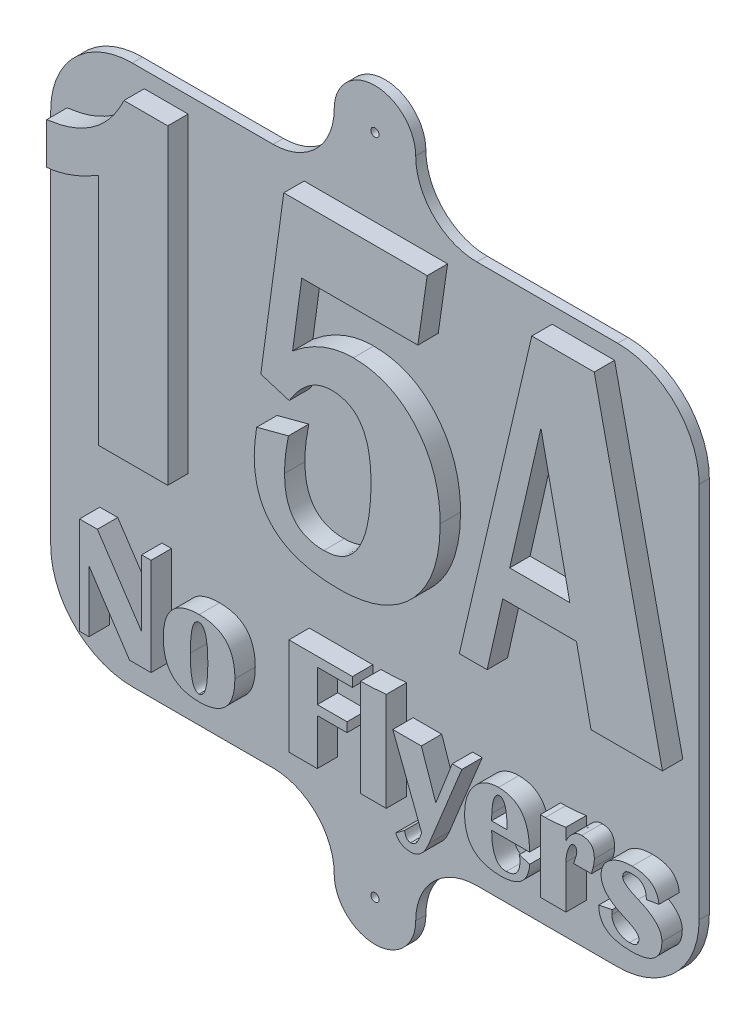
SolidWorks part; units mm, degrees
ref_plane "Front Plane" through (0, 0, 0) normal (0, 0, 1) x (1, 0, 0)
ref_plane "Top Plane" through (0, 0, 0) normal (0, 1, 0) x (1, 0, 0)
ref_plane "Right Plane" through (0, 0, 0) normal (1, 0, 0) x (0, 0, -1)
sketch "Sketch2" plane through (0, 0, 0) normal (0, 0, 1) x (1, 0, 0)
  line L0 (-33.1391, 3.1236) -> (-24.6504, 3.1236)
  line L1 (-43.75, -43.75) -> (43.75, -43.75)
  line L2 (-43.75, -43.75) -> (-43.75, 43.75)
  line L3 (-43.75, 43.75) -> (43.75, 43.75)
  line L4 (43.75, -43.75) -> (43.75, 43.75)
  line L6 (-43.75, 43.75) -> (-5.7811, 5.7811) construction
  line L7 (-35.4802, -17.7994) -> (-34.3196, -17.7994)
  line L8 (-24.6504, 41.3228) -> (-24.6504, 3.1236)
  line L9 (-24.6504, 3.1236) -> (-33.1391, 3.1236)
  line L10 (-33.1391, 3.1236) -> (-33.1391, 31.8144)
  line L11 (-39.5056, 29.485) -> (-39.5056, 34.5501)
  line L12 (-30.0304, 41.3228) -> (-24.6504, 41.3228)
  line L13 (7.1823, 41.3228) -> (6.0383, 33.3646)
  line L14 (6.0383, 33.3646) -> (-8.2118, 33.3646)
  line L15 (-8.2118, 33.3646) -> (-9.3392, 25.05)
  line L16 (-13.7411, 14.7541) -> (-9.8449, 15.782)
  line L17 (-9.7537, 19.5787) -> (-13.2354, 20.6481)
  line L18 (-13.2354, 20.6481) -> (-10.4169, 41.3228)
  line L19 (-10.4169, 41.3228) -> (7.1823, 41.3228)
  line L20 (27.6746, 41.3228) -> (36.0472, 3.1236)
  line L21 (36.0472, 3.1236) -> (27.285, 3.1236)
  line L22 (27.285, 3.1236) -> (25.4944, 11.6123)
  line L23 (25.4944, 11.6123) -> (16.4502, 11.6123)
  line L24 (16.4502, 11.6123) -> (14.5353, 3.1236)
  line L25 (14.5353, 3.1236) -> (11.1199, 3.1236)
  line L26 (11.1199, 3.1236) -> (20.0148, 41.3228)
  line L27 (20.0148, 41.3228) -> (27.6746, 41.3228)
  line L28 (17.3041, 15.3261) -> (24.682, 15.3261)
  line L29 (24.682, 15.3261) -> (21.134, 32.088)
  line L30 (21.134, 32.088) -> (17.3041, 15.3261)
  line L31 (-26.693, -5.8621) -> (-26.693, -17.7994)
  line L32 (-26.693, -17.7994) -> (-29.338, -17.7994)
  line L33 (-29.338, -17.7994) -> (-34.3196, -10.2687)
  line L34 (-34.3196, -10.2687) -> (-34.3196, -17.7994)
  line L35 (-34.3196, -17.7994) -> (-35.4802, -17.7994)
  line L36 (-35.4802, -17.7994) -> (-35.4802, -5.8621)
  line L37 (-35.4802, -5.8621) -> (-33.2886, -5.8621)
  line L38 (-33.2886, -5.8621) -> (-27.8536, -14.0327)
  line L39 (-27.8536, -14.0327) -> (-27.8536, -5.8621)
  line L40 (-27.8536, -5.8621) -> (-26.693, -5.8621)
  line L41 (-1.9895, -5.8621) -> (-1.9895, -7.0227)
  line L42 (-1.9895, -7.0227) -> (-6.3002, -7.0227)
  line L43 (-6.3002, -7.0227) -> (-6.3002, -11.0018)
  line L44 (-6.3002, -11.0018) -> (-2.6527, -11.0018)
  line L45 (-2.6527, -11.0018) -> (-2.6527, -12.1624)
  line L46 (-2.6527, -12.1624) -> (-6.3002, -12.1624)
  line L47 (-6.3002, -12.1624) -> (-6.3002, -17.7994)
  line L48 (-6.3002, -17.7994) -> (-9.7819, -17.7994)
  line L49 (-9.7819, -17.7994) -> (-9.7819, -5.8621)
  line L50 (-9.7819, -5.8621) -> (-1.9895, -5.8621)
  line L51 (2.1553, -5.6886) -> (2.1553, -17.7994)
  line L52 (2.1553, -17.7994) -> (-0.9948, -17.7994)
  line L53 (-0.9948, -17.7994) -> (-0.9948, -5.8621)
  line L54 (11.4399, -9.0123) -> (7.4012, -18.9133)
  line L55 (3.3081, -19.8226) -> (4.4091, -19.0221)
  line L56 (6.2717, -18.8408) -> (6.5075, -18.2372)
  line L57 (6.5075, -18.2372) -> (2.9584, -9.0123)
  line L58 (2.9584, -9.0123) -> (6.4634, -9.0123)
  line L59 (6.4634, -9.0123) -> (8.238, -14.1804)
  line L60 (8.238, -14.1804) -> (10.2586, -9.0123)
  line L61 (10.2586, -9.0123) -> (11.4399, -9.0123)
  line L62 (18.4706, -14.5612) -> (19.7555, -14.9368)
  line L63 (19.7374, -13.6545) -> (15.0874, -13.6545)
  line L64 (15.077, -12.6597) -> (16.9836, -12.6597)
  line L65 (15.1133, -11.8463) -> (15.077, -12.6597)
  line L66 (27.3355, -12.1624) -> (25.1517, -12.1624)
  line L67 (24.2061, -12.4965) -> (24.2061, -17.7994)
  line L68 (24.2061, -17.7994) -> (21.056, -17.7994)
  line L69 (21.056, -17.7994) -> (21.056, -9.0123)
  line L70 (21.056, -9.0123) -> (21.67, -9.0123)
  line L71 (24.2061, -8.7817) -> (24.2061, -10.2169)
  line L72 (35.6175, -11.2686) -> (34.0709, -11.5406)
  line L73 (28.2292, -15.0353) -> (29.8742, -14.7063)
  line L74 (-29.338, -17.7994) -> (-26.693, -17.7994)
  line L75 (11.1199, 3.1236) -> (14.5353, 3.1236)
  line L76 (27.285, 3.1236) -> (36.0472, 3.1236)
  line L77 (-9.7819, -17.7994) -> (-6.3002, -17.7994)
  line L78 (-0.9948, -17.7994) -> (2.1553, -17.7994)
  line L79 (6.339, -17.7994) -> (7.8556, -17.7994)
  line L80 (13.5471, 13.5471) -> (43.75, 43.75) construction
  line L81 (21.056, -17.7994) -> (24.2061, -17.7994)
  line L82 (9.9083, -9.9083) -> (43.75, -43.75) construction
  spline S0 degree 3 poles (-33.1391, 31.8144) (-34.1906, 31.1802) (-36.2341, 30.1453) (-38.456, 29.5713) (-39.5056, 29.485) knots 0 0 0 0 0.539332 1 1 1 1
  spline S1 degree 3 poles (-39.5056, 34.5501) (-38.4451, 34.6886) (-36.8913, 35.0188) (-35.0093, 35.8709) (-33.742, 36.6305) (-32.6145, 37.5733) (-31.2534, 39.0609) (-30.464, 40.3838) (-30.0304, 41.3228) knots 0 0 0 0 0.263349 0.386092 0.50611 0.625172 0.745757 1 1 1 1
  spline S2 degree 3 poles (-9.3392, 25.05) (-8.7632, 25.5267) (-7.8787, 26.1871) (-6.6199, 26.8894) (-5.6888, 27.3147) (-4.7523, 27.6494) (-3.4929, 27.9606) (-2.5292, 28.0565) (-1.8867, 28.0592) knots 0 0 0 0 0.273618 0.402083 0.526429 0.647547 0.765176 1 1 1 1
  spline S3 degree 3 poles (-1.8867, 28.0592) (-1.1408, 28.0481) (-0.0301, 27.967) (1.3791, 27.5874) (2.3756, 27.2174) (3.3149, 26.7244) (4.1996, 26.1209) (5.0326, 25.4142) (5.7975, 24.5994) (6.5002, 23.7132) (7.11, 22.7511) (7.6205, 21.7299) (8.0527, 20.6511) (8.3681, 19.5069) (8.6873, 17.8723) (8.7699, 16.6024) (8.7739, 15.7406) knots 0 0 0 0 0.122904 0.181635 0.23943 0.297339 0.355551 0.415172 0.476547 0.538982 0.600861 0.663434 0.72645 0.791596 0.858237 1 1 1 1
  spline S4 degree 3 poles (8.7739, 15.7406) (8.7755, 14.7846) (8.6868, 13.3764) (8.3232, 11.5769) (7.9641, 10.3288) (7.4741, 9.169) (6.909, 8.0702) (6.2105, 7.0658) (5.4251, 6.1354) (4.549, 5.2988) (3.5905, 4.5707) (2.5527, 3.9682) (1.4527, 3.4525) (0.2716, 3.067) (-1.4387, 2.6944) (-2.7758, 2.5967) (-3.6856, 2.593) knots 0 0 0 0 0.140185 0.205865 0.26878 0.330146 0.390105 0.449525 0.508998 0.56829 0.626685 0.684956 0.743842 0.804414 0.86661 1 1 1 1
  spline S5 degree 3 poles (-3.6856, 2.593) (-4.4974, 2.5877) (-5.6755, 2.6554) (-7.1848, 2.8877) (-8.1962, 3.1427) (-9.1394, 3.4364) (-9.9902, 3.8354) (-10.7656, 4.2887) (-11.462, 4.8138) (-12.0705, 5.4148) (-12.5954, 6.0856) (-13.0517, 6.8215) (-13.4099, 7.6356) (-13.6964, 8.5155) (-13.9617, 9.8198) (-14.0436, 10.8436) (-14.0395, 11.546) knots 0 0 0 0 0.15526 0.225408 0.291834 0.354702 0.414082 0.47121 0.526304 0.580516 0.634356 0.688946 0.745744 0.804099 0.865695 1 1 1 1
  spline S6 degree 3 poles (-14.0395, 11.546) (-14.0442, 12.0308) (-13.968, 13.1039) (-13.8394, 14.1714) (-13.7411, 14.7541) knots 0 0 0 0 0.450572 1 1 1 1
  spline S7 degree 3 poles (-9.8449, 15.782) (-9.9946, 15.047) (-10.2261, 13.6411) (-10.3233, 12.2193) (-10.3257, 11.546) knots 0 0 0 0 0.527123 1 1 1 1
  spline S8 degree 3 poles (-10.3257, 11.546) (-10.3201, 10.7021) (-10.2291, 9.4835) (-9.6932, 8.0432) (-9.1555, 7.2077) (-8.4633, 6.5493) (-7.2646, 5.9193) (-6.2165, 5.775) (-5.501, 5.7763) knots 0 0 0 0 0.295855 0.419781 0.532649 0.639755 0.749346 1 1 1 1
  spline S9 degree 3 poles (-5.501, 5.7763) (-5.0453, 5.7816) (-4.3712, 5.8422) (-3.5326, 6.1176) (-2.9627, 6.4023) (-2.439, 6.7696) (-1.9593, 7.2161) (-1.5308, 7.7439) (-1.1343, 8.3417) (-0.81, 9.0338) (-0.5074, 9.7953) (-0.2631, 10.6428) (-0.066, 11.5686) (0.0887, 12.5707) (0.2512, 14.0643) (0.2786, 15.2291) (0.2852, 16.0307) knots 0 0 0 0 0.10375 0.151958 0.199653 0.247862 0.29669 0.347938 0.401879 0.459116 0.521094 0.587794 0.659039 0.735879 0.817906 1 1 1 1
  spline S10 degree 3 poles (0.2852, 16.0307) (0.2866, 16.5977) (0.259, 17.4225) (0.1197, 18.4794) (-0.0109, 19.1881) (-0.1718, 19.8457) (-0.3934, 20.4368) (-0.6256, 20.9865) (-0.9235, 21.4664) (-1.2404, 21.901) (-1.6062, 22.271) (-2.0019, 22.5916) (-2.4512, 22.839) (-2.929, 23.0384) (-3.6371, 23.2319) (-4.1962, 23.2934) (-4.5809, 23.2843) knots 0 0 0 0 0.17174 0.249366 0.322555 0.389926 0.453974 0.513525 0.570203 0.624586 0.67606 0.727282 0.778237 0.830754 0.883736 1 1 1 1
  spline S11 degree 3 poles (-4.5809, 23.2843) (-5.0596, 23.2861) (-5.783, 23.1625) (-6.6885, 22.7745) (-7.3496, 22.3591) (-7.9872, 21.8328) (-8.8502, 20.9425) (-9.4002, 20.1459) (-9.7537, 19.5787) knots 0 0 0 0 0.215337 0.326397 0.442196 0.566126 0.69826 1 1 1 1
  spline S12 degree 3 poles (-20.8021, -8.6807) (-20.4583, -8.6807) (-19.9561, -8.7116) (-19.3169, -8.8346) (-18.8862, -8.9615) (-18.4897, -9.1247) (-18.1268, -9.3249) (-17.7979, -9.5622) (-17.5028, -9.8355) (-17.2447, -10.1473) (-17.021, -10.4945) (-16.8311, -10.8775) (-16.679, -11.2977) (-16.5615, -11.7534) (-16.438, -12.4287) (-16.4188, -12.96) (-16.4137, -13.3229) knots 0 0 0 0 0.140797 0.205276 0.266125 0.324294 0.38047 0.435417 0.489949 0.544674 0.600666 0.658689 0.719308 0.783277 0.851166 1 1 1 1
  spline S13 degree 3 poles (-16.4137, -13.3229) (-16.4188, -13.6858) (-16.438, -14.2172) (-16.5615, -14.8925) (-16.679, -15.3482) (-16.8311, -15.7684) (-17.021, -16.1513) (-17.2447, -16.4986) (-17.5028, -16.8104) (-17.7979, -17.0836) (-18.1268, -17.3209) (-18.4897, -17.5211) (-18.8862, -17.6844) (-19.3169, -17.8113) (-19.9561, -17.9342) (-20.4583, -17.9651) (-20.8021, -17.9652) knots 0 0 0 0 0.148834 0.216723 0.280692 0.341311 0.399334 0.455326 0.510051 0.564583 0.61953 0.675706 0.733875 0.794724 0.859203 1 1 1 1
  spline S14 degree 3 poles (-20.8021, -17.9652) (-21.1467, -17.9651) (-21.65, -17.9346) (-22.2907, -17.8108) (-22.7226, -17.685) (-23.1202, -17.5204) (-23.4846, -17.3216) (-23.8142, -17.0845) (-24.1065, -16.8086) (-24.3676, -16.4996) (-24.591, -16.1513) (-24.7803, -15.7679) (-24.9362, -15.3487) (-25.0539, -14.8927) (-25.1706, -14.2165) (-25.1998, -13.6864) (-25.2009, -13.3229) knots 0 0 0 0 0.141 0.205411 0.266534 0.324641 0.381066 0.435955 0.490171 0.545064 0.600996 0.658958 0.719635 0.783535 0.85129 1 1 1 1
  spline S15 degree 3 poles (-25.2009, -13.3229) (-25.1998, -12.9595) (-25.1706, -12.4294) (-25.0539, -11.7532) (-24.9362, -11.2971) (-24.7803, -10.878) (-24.591, -10.4946) (-24.3676, -10.1462) (-24.1065, -9.8373) (-23.8142, -9.5613) (-23.4846, -9.3243) (-23.1202, -9.1255) (-22.7226, -8.9608) (-22.2907, -8.8351) (-21.65, -8.7112) (-21.1467, -8.6807) (-20.8021, -8.6807) knots 0 0 0 0 0.14871 0.216465 0.280365 0.341042 0.399004 0.454936 0.509829 0.564045 0.618934 0.675359 0.733466 0.794589 0.859 1 1 1 1
  spline S16 degree 3 poles (-20.8125, -9.5096) (-20.8991, -9.5103) (-21.032, -9.5408) (-21.1834, -9.6429) (-21.2888, -9.75) (-21.3837, -9.8867) (-21.4718, -10.0519) (-21.5516, -10.2463) (-21.6197, -10.4717) (-21.6853, -10.7244) (-21.738, -11.0086) (-21.785, -11.3212) (-21.8203, -11.6645) (-21.8473, -12.0369) (-21.8828, -12.5927) (-21.8798, -13.0251) (-21.885, -13.3229) knots 0 0 0 0 0.061623 0.093987 0.128729 0.167924 0.211891 0.261732 0.317091 0.379205 0.447379 0.522509 0.604032 0.692727 0.788081 1 1 1 1
  spline S17 degree 3 poles (-21.885, -13.3229) (-21.8798, -13.6207) (-21.8828, -14.0532) (-21.8473, -14.6089) (-21.8203, -14.9813) (-21.785, -15.3246) (-21.738, -15.6373) (-21.6853, -15.9214) (-21.6197, -16.1742) (-21.5516, -16.3995) (-21.4718, -16.5939) (-21.3837, -16.7592) (-21.2888, -16.8959) (-21.1834, -17.003) (-21.032, -17.1051) (-20.8991, -17.1356) (-20.8125, -17.1362) knots 0 0 0 0 0.211919 0.307273 0.395968 0.477491 0.552621 0.620795 0.682909 0.738268 0.788109 0.832076 0.871271 0.906013 0.938377 1 1 1 1
  spline S18 degree 3 poles (-20.8125, -17.1362) (-20.7251, -17.1358) (-20.5908, -17.1058) (-20.4389, -17.0021) (-20.3306, -16.897) (-20.2367, -16.7583) (-20.1444, -16.5949) (-20.0668, -16.3988) (-19.9932, -16.1752) (-19.9332, -15.9208) (-19.8785, -15.6374) (-19.8331, -15.3244) (-19.7935, -14.9815) (-19.7666, -14.609) (-19.7378, -14.053) (-19.7307, -13.6209) (-19.7296, -13.3229) knots 0 0 0 0 0.062144 0.094462 0.129591 0.16873 0.212928 0.262698 0.318165 0.380042 0.448118 0.523141 0.604614 0.693183 0.788367 1 1 1 1
  spline S19 degree 3 poles (-19.7296, -13.3229) (-19.7307, -13.025) (-19.7378, -12.5929) (-19.7666, -12.0369) (-19.7935, -11.6643) (-19.8331, -11.3215) (-19.8785, -11.0085) (-19.9332, -10.725) (-19.9932, -10.4707) (-20.0668, -10.247) (-20.1444, -10.051) (-20.2367, -9.8875) (-20.3306, -9.7489) (-20.4389, -9.6437) (-20.5908, -9.54) (-20.7251, -9.51) (-20.8125, -9.5096) knots 0 0 0 0 0.211633 0.306817 0.395386 0.476859 0.551882 0.619958 0.681835 0.737302 0.787072 0.83127 0.870409 0.905538 0.937856 1 1 1 1
  spline S20 degree 3 poles (-0.9948, -5.8621) (-0.5143, -5.8633) (0.5373, -5.8234) (1.5862, -5.7414) (2.1553, -5.6886) knots 0 0 0 0 0.45666 1 1 1 1
  spline S21 degree 3 poles (7.4012, -18.9133) (7.2714, -19.2193) (7.0685, -19.6552) (6.7116, -20.1492) (6.4408, -20.441) (6.1481, -20.6664) (5.736, -20.8874) (5.3907, -20.9506) (5.163, -20.9495) knots 0 0 0 0 0.310559 0.44483 0.566674 0.680331 0.787619 1 1 1 1
  spline S22 degree 3 poles (5.163, -20.9495) (4.9526, -20.9482) (4.6445, -20.9201) (4.2629, -20.801) (4.0155, -20.6728) (3.7919, -20.5159) (3.5326, -20.2444) (3.3847, -19.9997) (3.3081, -19.8226) knots 0 0 0 0 0.27306 0.397686 0.515848 0.632977 0.750149 1 1 1 1
  spline S23 degree 3 poles (4.4091, -19.0221) (4.4312, -19.1594) (4.4696, -19.3553) (4.5682, -19.5862) (4.653, -19.7212) (4.7566, -19.8257) (4.9173, -19.9259) (5.0584, -19.955) (5.1526, -19.9547) knots 0 0 0 0 0.318404 0.451751 0.571535 0.680293 0.784804 1 1 1 1
  spline S24 degree 3 poles (5.1526, -19.9547) (5.2658, -19.9548) (5.4361, -19.9168) (5.6427, -19.8016) (5.7862, -19.6745) (5.9231, -19.5161) (6.1003, -19.2427) (6.2076, -19.0087) (6.2717, -18.8408) knots 0 0 0 0 0.201356 0.305645 0.419429 0.541915 0.678834 1 1 1 1
  spline S25 degree 3 poles (19.7555, -14.9368) (19.7408, -15.1753) (19.6964, -15.5234) (19.575, -15.962) (19.4643, -16.2595) (19.3266, -16.5335) (19.1623, -16.7831) (18.9748, -17.0109) (18.7618, -17.2137) (18.5224, -17.3908) (18.2604, -17.5477) (17.9708, -17.6759) (17.6579, -17.7827) (17.3197, -17.8647) (16.8212, -17.9468) (16.4312, -17.9617) (16.165, -17.9652) knots 0 0 0 0 0.135124 0.197408 0.256874 0.31428 0.370323 0.425441 0.480677 0.536122 0.593459 0.652878 0.71477 0.780114 0.84936 1 1 1 1
  spline S26 degree 3 poles (16.165, -17.9652) (15.8214, -17.9641) (15.3195, -17.9348) (14.6797, -17.8179) (14.2475, -17.7007) (13.8512, -17.5439) (13.4875, -17.3551) (13.1594, -17.1279) (12.8642, -16.8681) (12.606, -16.572) (12.3819, -16.2432) (12.192, -15.8797) (12.036, -15.4812) (11.9191, -15.0474) (11.8013, -14.4051) (11.7728, -13.9014) (11.7715, -13.5561) knots 0 0 0 0 0.14445 0.210484 0.272978 0.332263 0.389223 0.444774 0.499517 0.554021 0.609366 0.666326 0.725949 0.788792 0.854827 1 1 1 1
  spline S27 degree 3 poles (11.7715, -13.5561) (11.7707, -13.2147) (11.8053, -12.7114) (11.9257, -12.0622) (12.057, -11.6105) (12.2191, -11.1815) (12.4234, -10.7797) (12.6592, -10.398) (12.933, -10.0457) (13.2336, -9.726) (13.5574, -9.4451) (13.9025, -9.2088) (14.2686, -9.0155) (14.6541, -8.8637) (15.2056, -8.7209) (15.6372, -8.6787) (15.9293, -8.6807) knots 0 0 0 0 0.142686 0.210299 0.275652 0.339072 0.401711 0.463814 0.526344 0.587887 0.647011 0.705185 0.762348 0.819731 0.877957 1 1 1 1
  spline S28 degree 3 poles (15.9293, -8.6807) (16.229, -8.677) (16.666, -8.7162) (17.2215, -8.8439) (17.5942, -8.9838) (17.9406, -9.1567) (18.2546, -9.3737) (18.5412, -9.6276) (18.7946, -9.9222) (19.0202, -10.2545) (19.2099, -10.6274) (19.3742, -11.0374) (19.5077, -11.4857) (19.6103, -11.9737) (19.7133, -12.6984) (19.7356, -13.2655) (19.7374, -13.6545) knots 0 0 0 0 0.125618 0.183354 0.238609 0.292242 0.345404 0.398269 0.452462 0.508033 0.566369 0.627661 0.693111 0.762396 0.836691 1 1 1 1
  spline S29 degree 3 poles (15.0874, -13.6545) (15.0879, -13.9267) (15.1007, -14.3221) (15.1453, -14.83) (15.1942, -15.1708) (15.2585, -15.484) (15.3363, -15.7704) (15.4251, -16.0306) (15.5323, -16.2624) (15.6504, -16.4683) (15.7837, -16.6473) (15.9314, -16.7987) (16.0947, -16.9226) (16.2717, -17.0195) (16.5331, -17.1113) (16.7428, -17.1378) (16.8852, -17.1362) knots 0 0 0 0 0.186873 0.271403 0.349872 0.423116 0.490705 0.553511 0.611599 0.665791 0.716179 0.764386 0.810506 0.856398 0.902335 1 1 1 1
  spline S30 degree 3 poles (16.8852, -17.1362) (17.0171, -17.1368) (17.2099, -17.1222) (17.4552, -17.0708) (17.62, -17.0142) (17.7744, -16.9495) (17.9117, -16.8616) (18.039, -16.7624) (18.1518, -16.6462) (18.2525, -16.5144) (18.3363, -16.3662) (18.4112, -16.2042) (18.4652, -16.0247) (18.5131, -15.8322) (18.5596, -15.5458) (18.5656, -15.3212) (18.5691, -15.1674) knots 0 0 0 0 0.133243 0.194893 0.252873 0.309166 0.363677 0.417128 0.472078 0.526909 0.584414 0.64381 0.707042 0.773535 0.844298 1 1 1 1
  spline S31 degree 2 poles (18.5691, -15.1674) (18.5649, -14.8572) (18.4706, -14.5612) knots 0 0 0 1 1 1
  spline S32 degree 3 poles (16.9836, -12.6597) (16.9866, -12.4135) (16.9766, -12.0567) (16.9511, -11.5975) (16.9304, -11.2895) (16.8943, -11.0066) (16.859, -10.7473) (16.8066, -10.5142) (16.7586, -10.3033) (16.6954, -10.1183) (16.6264, -9.9578) (16.5512, -9.8207) (16.4692, -9.7074) (16.3767, -9.6199) (16.2456, -9.5345) (16.1307, -9.511) (16.0562, -9.5096) knots 0 0 0 0 0.210509 0.305164 0.393283 0.474337 0.549002 0.616921 0.678527 0.733866 0.783799 0.827762 0.86734 0.902859 0.936045 1 1 1 1
  spline S33 degree 3 poles (16.0562, -9.5096) (15.9892, -9.5132) (15.8853, -9.5258) (15.7641, -9.5907) (15.6783, -9.6551) (15.5986, -9.738) (15.5262, -9.841) (15.4596, -9.9604) (15.3966, -10.097) (15.3401, -10.252) (15.2919, -10.4264) (15.248, -10.6184) (15.2095, -10.8284) (15.176, -11.0574) (15.1365, -11.3981) (15.1223, -11.664) (15.1133, -11.8463) knots 0 0 0 0 0.0748 0.112303 0.150418 0.192873 0.238621 0.288971 0.343544 0.404439 0.4708 0.54315 0.621646 0.70641 0.798486 1 1 1 1
  spline S34 degree 3 poles (25.1517, -12.1624) (25.19, -12.0102) (25.2615, -11.7514) (25.3476, -11.4971) (25.3874, -11.393) knots 0 0 0 0 0.584792 1 1 1 1
  spline S35 degree 3 poles (25.3874, -11.393) (25.4358, -11.2821) (25.4998, -11.0658) (25.5354, -10.8426) (25.5325, -10.7376) knots 0 0 0 0 0.535657 1 1 1 1
  spline S36 degree 3 poles (25.5325, -10.7376) (25.5283, -10.656) (25.5257, -10.536) (25.4764, -10.3962) (25.4344, -10.3118) (25.371, -10.2504) (25.2682, -10.1883) (25.1759, -10.1695) (25.1128, -10.1728) knots 0 0 0 0 0.309173 0.439003 0.553293 0.658441 0.764331 1 1 1 1
  spline S37 degree 3 poles (25.1128, -10.1728) (25.0554, -10.169) (24.9722, -10.2032) (24.8702, -10.2775) (24.7948, -10.3626) (24.715, -10.4666) (24.6429, -10.5975) (24.5657, -10.7484) (24.472, -10.9831) (24.3662, -11.2956) (24.2389, -11.8192) (24.2073, -12.2251) (24.2061, -12.4965) knots 0 0 0 0 0.063446 0.100118 0.143357 0.192645 0.249623 0.313545 0.386037 0.537847 0.689909 1 1 1 1
  spline S38 degree 3 poles (21.67, -9.0123) (22.0625, -9.0089) (22.9121, -8.9683) (23.7546, -8.8522) (24.2061, -8.7817) knots 0 0 0 0 0.462038 1 1 1 1
  spline S39 degree 3 poles (24.2061, -10.2169) (24.3239, -9.9808) (24.5245, -9.6576) (24.835, -9.2828) (25.0712, -9.0632) (25.3197, -8.8903) (25.6671, -8.7313) (25.9469, -8.6775) (26.1335, -8.6807) knots 0 0 0 0 0.304429 0.437467 0.560958 0.675739 0.785499 1 1 1 1
  spline S40 degree 3 poles (26.1335, -8.6807) (26.3637, -8.6777) (26.6993, -8.7214) (27.0848, -8.9117) (27.3112, -9.1049) (27.4838, -9.3554) (27.6565, -9.7848) (27.6874, -10.1507) (27.6878, -10.4034) knots 0 0 0 0 0.260755 0.373235 0.481088 0.593056 0.713264 1 1 1 1
  spline S41 degree 3 poles (27.6878, -10.4034) (27.6877, -10.5666) (27.6542, -10.9177) (27.5729, -11.2606) (27.522, -11.4422) knots 0 0 0 0 0.463654 1 1 1 1
  spline S42 degree 3 poles (27.522, -11.4422) (27.4964, -11.5422) (27.4393, -11.7836) (27.3708, -12.022) (27.3355, -12.1624) knots 0 0 0 0 0.41636 1 1 1 1
  spline S43 degree 3 poles (34.0709, -11.5406) (34.0702, -11.3943) (34.0575, -11.1813) (34.0128, -10.9091) (33.9633, -10.726) (33.8986, -10.5578) (33.8212, -10.4036) (33.729, -10.2654) (33.6259, -10.138) (33.5022, -10.0314) (33.3698, -9.9328) (33.221, -9.8531) (33.0582, -9.7882) (32.8823, -9.7365) (32.62, -9.6867) (32.414, -9.6773) (32.2731, -9.6754) knots 0 0 0 0 0.147681 0.214882 0.2781 0.338798 0.396487 0.451844 0.506302 0.561239 0.616155 0.672707 0.730972 0.79275 0.857534 1 1 1 1
  spline S44 degree 3 poles (32.2731, -9.6754) (32.1106, -9.6714) (31.8799, -9.6976) (31.603, -9.7921) (31.443, -9.8942) (31.3187, -10.0257) (31.1968, -10.2506) (31.1703, -10.4482) (31.1695, -10.5821) knots 0 0 0 0 0.298126 0.42318 0.534592 0.643534 0.752244 1 1 1 1
  spline S45 degree 3 poles (31.1695, -10.5821) (31.1662, -10.7076) (31.2531, -10.8924) (31.4418, -11.1129) (31.6535, -11.2906) (31.9227, -11.471) (32.3931, -11.7317) (32.7856, -11.9083) (33.0684, -12.0225) knots 0 0 0 0 0.146898 0.239583 0.349937 0.480022 0.631095 1 1 1 1
  spline S46 degree 3 poles (33.0684, -12.0225) (33.3008, -12.1134) (33.6314, -12.2687) (34.0537, -12.4852) (34.3373, -12.6527) (34.5994, -12.8224) (34.8383, -12.9997) (35.0567, -13.1791) (35.2492, -13.3677) (35.4211, -13.5587) (35.5698, -13.7561) (35.6947, -13.9596) (35.7984, -14.1664) (35.8817, -14.3782) (35.9504, -14.6709) (35.9827, -14.8944) (35.9776, -15.0456) knots 0 0 0 0 0.167902 0.245928 0.319429 0.389588 0.456112 0.519695 0.579733 0.637392 0.692634 0.745891 0.797901 0.848334 0.898683 1 1 1 1
  spline S47 degree 3 poles (35.9776, -15.0456) (35.9768, -15.2746) (35.9505, -15.6098) (35.8528, -16.0353) (35.7486, -16.3221) (35.6151, -16.5861) (35.4553, -16.8296) (35.2597, -17.0454) (35.0387, -17.2422) (34.7845, -17.4121) (34.5044, -17.564) (34.1922, -17.6868) (33.8532, -17.7914) (33.4832, -17.8667) (32.9347, -17.9451) (32.506, -17.968) (32.2109, -17.9652) knots 0 0 0 0 0.126278 0.184476 0.240198 0.294062 0.347272 0.400209 0.454175 0.510028 0.568388 0.629474 0.69468 0.763773 0.837359 1 1 1 1
  spline S48 degree 3 poles (32.2109, -17.9652) (31.8993, -17.9688) (31.4469, -17.9438) (30.8665, -17.8682) (30.4766, -17.7866) (30.1154, -17.6891) (29.7879, -17.5601) (29.4888, -17.4141) (29.2241, -17.2389) (28.9879, -17.0441) (28.784, -16.8247) (28.6124, -16.5821) (28.4702, -16.3172) (28.3625, -16.0284) (28.2556, -15.6023) (28.2294, -15.2651) (28.2292, -15.0353) knots 0 0 0 0 0.165837 0.241022 0.311462 0.377854 0.440027 0.498642 0.554765 0.608642 0.661358 0.713803 0.766474 0.821053 0.877491 1 1 1 1
  spline S49 degree 2 poles (29.8742, -14.7063) (29.8441, -14.9749) (29.8431, -15.2451) knots 0 0 0 1 1 1
  spline S50 degree 3 poles (29.8431, -15.2451) (29.842, -15.369) (29.8653, -15.553) (29.9299, -15.7903) (30.0015, -15.9603) (30.0919, -16.1241) (30.2053, -16.2796) (30.3353, -16.4312) (30.4841, -16.5737) (30.6458, -16.7064) (30.8204, -16.8185) (30.9985, -16.9198) (31.1868, -16.9956) (31.38, -17.0603) (31.6522, -17.1168) (31.8618, -17.1401) (32.0037, -17.1362) knots 0 0 0 0 0.116688 0.174248 0.231629 0.290383 0.350562 0.412991 0.478719 0.544799 0.610146 0.674364 0.737953 0.801375 0.866457 1 1 1 1
  spline S51 degree 3 poles (32.0037, -17.1362) (32.1722, -17.1329) (32.418, -17.1188) (32.7054, -17.0078) (32.8739, -16.9017) (33.0032, -16.7609) (33.1324, -16.5226) (33.1588, -16.3106) (33.159, -16.1674) knots 0 0 0 0 0.295704 0.419895 0.532859 0.639211 0.748836 1 1 1 1
  spline S52 degree 3 poles (33.159, -16.1674) (33.161, -16.0444) (33.0779, -15.8615) (32.8921, -15.6451) (32.6854, -15.4698) (32.4239, -15.2886) (31.9661, -15.0248) (31.5832, -14.8448) (31.3068, -14.7296) knots 0 0 0 0 0.14705 0.2399 0.349931 0.479725 0.631272 1 1 1 1
  spline S53 degree 3 poles (31.3068, -14.7296) (31.087, -14.6319) (30.7649, -14.4859) (30.3624, -14.2634) (30.0892, -14.0946) (29.8386, -13.9215) (29.608, -13.7451) (29.4011, -13.5606) (29.2135, -13.3724) (29.0499, -13.1767) (28.906, -12.9778) (28.7868, -12.7715) (28.6869, -12.5616) (28.612, -12.3449) (28.5388, -12.0491) (28.5152, -11.8206) (28.5168, -11.6676) knots 0 0 0 0 0.164237 0.240988 0.313756 0.383223 0.448755 0.511784 0.572202 0.62992 0.685678 0.739546 0.792268 0.844076 0.895668 1 1 1 1
  spline S54 degree 3 poles (28.5168, -11.6676) (28.513, -11.4686) (28.5496, -11.1746) (28.6612, -10.8003) (28.7783, -10.5371) (28.9308, -10.289) (29.1156, -10.0546) (29.336, -9.8362) (29.5865, -9.6333) (29.8617, -9.4479) (30.1589, -9.2856) (30.477, -9.153) (30.8107, -9.0364) (31.1661, -8.953) (31.6745, -8.8672) (32.0698, -8.8483) (32.3378, -8.8465) knots 0 0 0 0 0.112419 0.166553 0.220612 0.27503 0.331076 0.389155 0.450317 0.51337 0.576815 0.641654 0.70829 0.776711 0.848084 1 1 1 1
  spline S55 degree 3 poles (32.3378, -8.8465) (32.5731, -8.8473) (32.9169, -8.8641) (33.3578, -8.9273) (33.6587, -8.9915) (33.9376, -9.0768) (34.1969, -9.1798) (34.4336, -9.3059) (34.6521, -9.4469) (34.8476, -9.6095) (35.0236, -9.7883) (35.1734, -9.9908) (35.3063, -10.2087) (35.4192, -10.4461) (35.5363, -10.7982) (35.5973, -11.076) (35.6175, -11.2686) knots 0 0 0 0 0.15521 0.226574 0.293602 0.35792 0.418734 0.477331 0.534516 0.589938 0.644715 0.699619 0.755589 0.812912 0.87253 1 1 1 1
  point P0 (0, 0)
  dimension "D1" = 87.5
  dimension "D2" = 87.5
extrude "Boss-Extrude3" add sketch "Sketch2" along normal blind 2.5 contours S1 L11 S0 L10 L0 L8 L12 | S11 S10 S9 S8 S7 L16 S6 S5 S4 S3 S2 L15 L14 L13 L19 L18 L17 | L27 L26 L25 L24 L23 L22 L21 L20 L30 L29 L28 | L40 L39 L38 L37 L36 L7 L34 L33 L32 L31 | S15 S14 S13 S12 S19 S18 S17 S16 | L50 L49 L48 L47 L46 L45 L44 L43 L42 L41 | S20 L53 L52 L51 | L57 L79 L54 L61 L60 L59 L58 | S24 S23 L55 S22 S21 L54 L79 L57 L56 | S31 S30 S29 L63 S28 S27 S26 S25 L62 S33 S32 L64 L65 | S42 S41 S40 S39 L71 S38 L70 L69 L68 L67 S37 S36 S35 S34 L66 | S55 S54 S53 S52 S51 S50 S49 L73 S48 S47 S46 S45 S44 S43 L72
sketch "Sketch3" plane through (0, 0, 0) normal (0, 0, 1) x (1, 0, 0)
  line L0 (-10.4169, 41.3228) -> (7.1823, 41.3228) construction
  line L1 (-41.5056, -22.9495) -> (38.0472, -22.9495)
  line L2 (-41.5056, -22.9495) -> (-41.5056, 43.3228)
  line L3 (-41.5056, 43.3228) -> (38.0472, 43.3228)
  line L4 (38.0472, -22.9495) -> (38.0472, 43.3228)
  line L5 (-39.5056, 29.485) -> (-39.5056, 34.5501) construction
  line L6 (-1.7292, 43.3228) -> (-6.7292, 43.3228)
  line L8 (-2.2292, 50.8228) -> (-1.2292, 50.8228)
  line L10 (3.2708, 43.3228) -> (-1.7292, 43.3228)
  line L11 (-41.5056, 43.3228) -> (-41.5056, -22.9495)
  line L12 (-41.5056, 10.1866) -> (-38.0273, 10.1866)
  arc A0 (3.2708, 50.8228) -> (-6.7292, 50.8228) centre (-1.7292, 50.8228) ccw
  arc A1 (-6.7292, 50.8228) -> (-14.2292, 43.3228) centre (-14.2292, 50.8228) cw
  arc A2 (3.2708, 50.8228) -> (10.7708, 43.3228) centre (10.7708, 50.8228) ccw
  circle A3 centre (-1.7292, 50.8228) radius 0.5
  circle A4 centre (-1.7292, -30.4495) radius 0.5
  arc A5 (3.2708, -30.4495) -> (10.7708, -22.9495) centre (10.7708, -30.4495) cw
  arc A6 (3.2708, -30.4495) -> (-6.7292, -30.4495) centre (-1.7292, -30.4495) cw
  arc A7 (-6.7292, -30.4495) -> (-14.2292, -22.9495) centre (-14.2292, -30.4495) ccw
  point P0 (0, 0)
  dimension "D1" = 2
  dimension "D2" = 2
  dimension "D3" = 2
  dimension "D4" = 2
  dimension "D6" = 10
  dimension "D7" = 7.5
extrude "Boss-Extrude4" add sketch "Sketch3" against normal blind 1.25 contours A2 A0 A1 L3 A3 | L1 L4 L3 L2 | A7 A6 A5 L1 A4
fillet "Fillet1" radius 10 4 edges at (-41.5056, -22.9495, -0.625) (38.0472, -22.9495, -0.625) (38.0472, 43.3228, -0.625) (-41.5056, 43.3228, -0.625)
